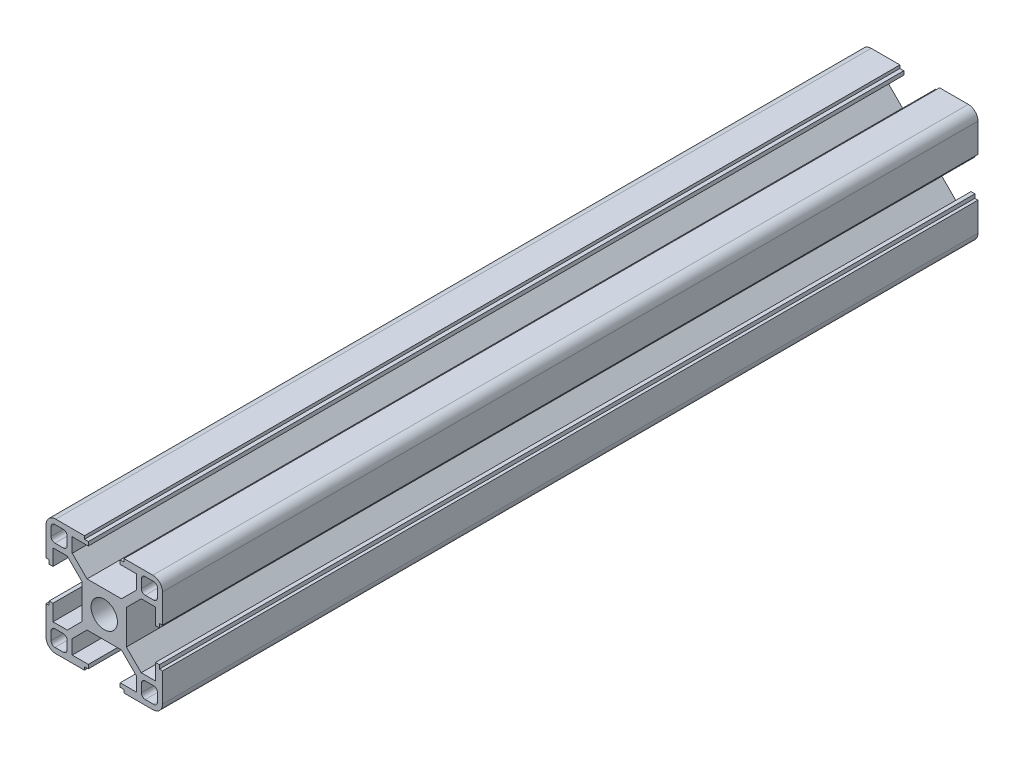
SolidWorks part; units mm, degrees
material "6061-T6 (SS)"
ref_plane "前视基准面" through (0, 0, 0) normal (0, 0, 1) x (1, 0, 0)
ref_plane "上视基准面" through (0, 0, 0) normal (0, 1, 0) x (1, 0, 0)
ref_plane "右视基准面" through (0, 0, 0) normal (1, 0, 0) x (0, 0, -1)
sketch "Sketch1" plane through (0, 0, 0) normal (0, 0, 1) x (1, 0, 0)
  line L0 (-5.1, 15) -> (-5.1, 14.2)
  line L1 (-12.5, -15) -> (12.5, -15)
  line L2 (-15, -12.5) -> (-15, 12.5)
  line L3 (-12.5, 15) -> (12.5, 15)
  line L4 (15, -12.5) -> (15, 12.5)
  line L5 (-15, -15) -> (15, 15) construction
  line L6 (-15, 15) -> (15, -15) construction
  line L7 (-5.1, 14.2) -> (-4.1, 14.2)
  line L8 (-4.1, 14.2) -> (-4.1, 13.2)
  line L9 (-4.1, 13.2) -> (-8.25, 13.2)
  line L10 (-8.25, 13.2) -> (-8.25, 9.5228)
  line L11 (-8.25, 9.5228) -> (-4.4272, 5.7)
  line L12 (-4.4272, 5.7) -> (4.4272, 5.7)
  line L13 (-5.1, 15) -> (5.1, 15)
  line L14 (0, 15) -> (0, 5.7) construction
  line L15 (8.25, 9.5228) -> (4.4272, 5.7)
  line L16 (8.25, 13.2) -> (8.25, 9.5228)
  line L17 (4.1, 13.2) -> (8.25, 13.2)
  line L18 (4.1, 14.2) -> (4.1, 13.2)
  line L19 (5.1, 14.2) -> (4.1, 14.2)
  line L20 (5.1, 15) -> (5.1, 14.2)
  line L21 (15, 5.1) -> (14.2, 5.1)
  line L22 (14.2, 5.1) -> (14.2, 4.1)
  line L23 (14.2, 4.1) -> (13.2, 4.1)
  line L24 (13.2, 4.1) -> (13.2, 8.25)
  line L25 (13.2, 8.25) -> (9.5228, 8.25)
  line L26 (9.5228, 8.25) -> (5.7, 4.4272)
  line L27 (5.7, 4.4272) -> (5.7, -4.4272)
  line L28 (15, 5.1) -> (15, -5.1)
  line L29 (9.5228, -8.25) -> (5.7, -4.4272)
  line L30 (13.2, -8.25) -> (9.5228, -8.25)
  line L31 (13.2, -4.1) -> (13.2, -8.25)
  line L32 (14.2, -4.1) -> (13.2, -4.1)
  line L33 (14.2, -5.1) -> (14.2, -4.1)
  line L34 (15, -5.1) -> (14.2, -5.1)
  line L35 (15, 0) -> (5.7, 0) construction
  line L36 (5.1, -15) -> (5.1, -14.2)
  line L37 (5.1, -14.2) -> (4.1, -14.2)
  line L38 (4.1, -14.2) -> (4.1, -13.2)
  line L39 (4.1, -13.2) -> (8.25, -13.2)
  line L40 (8.25, -13.2) -> (8.25, -9.5228)
  line L41 (8.25, -9.5228) -> (4.4272, -5.7)
  line L42 (4.4272, -5.7) -> (-4.4272, -5.7)
  line L43 (5.1, -15) -> (-5.1, -15)
  line L44 (-8.25, -9.5228) -> (-4.4272, -5.7)
  line L45 (-8.25, -13.2) -> (-8.25, -9.5228)
  line L46 (-4.1, -13.2) -> (-8.25, -13.2)
  line L47 (-4.1, -14.2) -> (-4.1, -13.2)
  line L48 (-5.1, -14.2) -> (-4.1, -14.2)
  line L49 (-5.1, -15) -> (-5.1, -14.2)
  line L50 (0, -15) -> (0, -5.7) construction
  line L51 (-15, -5.1) -> (-14.2, -5.1)
  line L52 (-14.2, -5.1) -> (-14.2, -4.1)
  line L53 (-14.2, -4.1) -> (-13.2, -4.1)
  line L54 (-13.2, -4.1) -> (-13.2, -8.25)
  line L55 (-13.2, -8.25) -> (-9.5228, -8.25)
  line L56 (-9.5228, -8.25) -> (-5.7, -4.4272)
  line L57 (-5.7, -4.4272) -> (-5.7, 4.4272)
  line L58 (-15, -5.1) -> (-15, 5.1)
  line L59 (-9.5228, 8.25) -> (-5.7, 4.4272)
  line L60 (-13.2, 8.25) -> (-9.5228, 8.25)
  line L61 (-13.2, 4.1) -> (-13.2, 8.25)
  line L62 (-14.2, 4.1) -> (-13.2, 4.1)
  line L63 (-14.2, 5.1) -> (-14.2, 4.1)
  line L64 (-15, 5.1) -> (-14.2, 5.1)
  line L65 (-15, 0) -> (-5.7, 0) construction
  line L66 (0, 0) -> (0, 5.7) construction
  circle A0 centre (0, 0) radius 3.4
  arc A1 (-12.5, -15) -> (-15, -12.5) centre (-12.5, -12.5) cw
  arc A2 (12.5, -15) -> (15, -12.5) centre (12.5, -12.5) ccw
  arc A3 (12.5, 15) -> (15, 12.5) centre (12.5, 12.5) cw
  arc A4 (-15, 12.5) -> (-12.5, 15) centre (-12.5, 12.5) cw
  point P0 (0, 0)
  dimension "D3" = 6.8
  dimension "D12" = 2.5
  dimension "D1" = 30
  dimension "D2" = 30
  dimension "D4" = 16.5
  dimension "D5" = 8.2
  dimension "D6" = 10.2
  dimension "D7" = 7.5
  dimension "D9" = 1.8
  dimension "D10" = 1.8
  dimension "D11" = 0.8
  dimension "D8" = 4
extrude "Extrude1" add sketch "Sketch1" along normal blind 210 contours A4 L2 L64 L63 L62 L61 L60 L59 L57 L56 L55 L54 L53 L52 L51 A1 L1 L49 L48 L47 L46 L45 L44 L42 L41 L40 L39 L38 L37 L36 A2 L4 L34 L33 L32 L31 L30 L29 L27 L26 L25 L24 L23 L22 L21 A3 L3 L20
sketch "Sketch2" plane through (0, 0, 210) normal (0, 0, 1) x (1, 0, 0)
  line L0 (13.7, 12.7) -> (13.7, 10.55)
  line L1 (-12.7, 13.7) -> (-10.55, 13.7)
  line L2 (-13.7, 12.7) -> (-13.7, 10.55)
  line L3 (-12.7, 9.55) -> (-10.55, 9.55)
  line L4 (-9.55, 12.7) -> (-9.55, 10.55)
  line L5 (-13.7, 13.7) -> (-9.55, 9.55) construction
  line L6 (-13.7, 9.55) -> (-9.55, 13.7) construction
  line L7 (12.7, 13.7) -> (10.55, 13.7)
  line L8 (9.55, 12.7) -> (9.55, 10.55)
  line L9 (12.7, 9.55) -> (10.55, 9.55)
  line L10 (12.7, -13.7) -> (10.55, -13.7)
  line L11 (13.7, -12.7) -> (13.7, -10.55)
  line L12 (12.7, -9.55) -> (10.55, -9.55)
  line L13 (9.55, -12.7) -> (9.55, -10.55)
  line L14 (-13.7, -12.7) -> (-13.7, -10.55)
  line L15 (-12.7, -13.7) -> (-10.55, -13.7)
  line L16 (-9.55, -12.7) -> (-9.55, -10.55)
  line L17 (-12.7, -9.55) -> (-10.55, -9.55)
  line L18 (0, 0) -> (-9.55, 9.55) construction
  line L19 (-12.5, 15) -> (-5.1, 15) construction
  line L20 (-15, 5.1) -> (-15, 12.5) construction
  line L21 (-13.2, 8.25) -> (-9.5228, 8.25) construction
  line L22 (-8.25, 13.2) -> (-8.25, 9.5228) construction
  arc A0 (-13.7, -12.7) -> (-12.7, -13.7) centre (-12.7, -12.7) ccw
  arc A1 (-10.55, -13.7) -> (-9.55, -12.7) centre (-10.55, -12.7) ccw
  arc A2 (-9.55, -10.55) -> (-10.55, -9.55) centre (-10.55, -10.55) ccw
  arc A3 (-13.7, -10.55) -> (-12.7, -9.55) centre (-12.7, -10.55) cw
  arc A4 (13.7, -10.55) -> (12.7, -9.55) centre (12.7, -10.55) ccw
  arc A5 (12.7, -13.7) -> (13.7, -12.7) centre (12.7, -12.7) ccw
  arc A6 (10.55, -13.7) -> (9.55, -12.7) centre (10.55, -12.7) cw
  arc A7 (10.55, -9.55) -> (9.55, -10.55) centre (10.55, -10.55) ccw
  arc A8 (13.7, 12.7) -> (12.7, 13.7) centre (12.7, 12.7) ccw
  arc A9 (13.7, 10.55) -> (12.7, 9.55) centre (12.7, 10.55) cw
  arc A10 (9.55, 10.55) -> (10.55, 9.55) centre (10.55, 10.55) ccw
  arc A11 (10.55, 13.7) -> (9.55, 12.7) centre (10.55, 12.7) ccw
  arc A12 (-10.55, 13.7) -> (-9.55, 12.7) centre (-10.55, 12.7) cw
  arc A13 (-10.55, 9.55) -> (-9.55, 10.55) centre (-10.55, 10.55) ccw
  arc A14 (-13.7, 10.55) -> (-12.7, 9.55) centre (-12.7, 10.55) ccw
  arc A15 (-12.7, 13.7) -> (-13.7, 12.7) centre (-12.7, 12.7) ccw
  point P0 (-11.625, 11.625)
  dimension "D2" = 1
  dimension "D3" = 1.3
  dimension "D4" = 1.3
  dimension "D5" = 1.3
  dimension "D6" = 1.3
  dimension "D1" = 4
extrude "Extrude2" cut sketch "Sketch2" against normal through all
